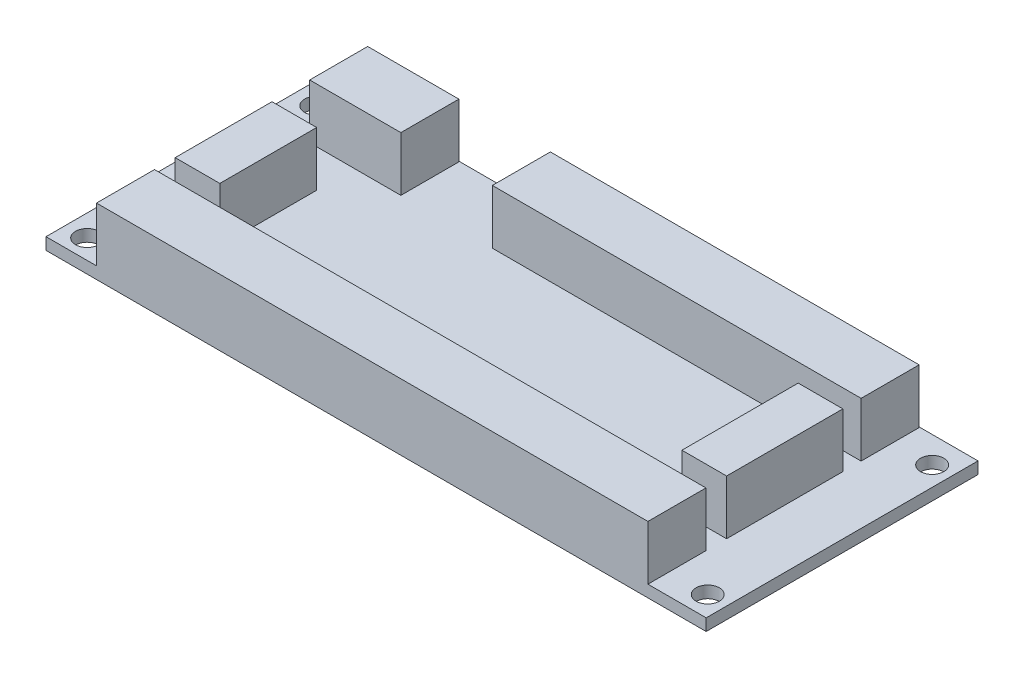
SolidWorks part; units mm, degrees
ref_plane "Front Plane" through (0, 0, 0) normal (0, 0, 1) x (1, 0, 0)
ref_plane "Top Plane" through (0, 0, 0) normal (0, 1, 0) x (1, 0, 0)
ref_plane "Right Plane" through (0, 0, 0) normal (1, 0, 0) x (0, 0, -1)
sketch "Sketch1" plane through (0, 0, 0) normal (0, 1, 0) x (1, 0, 0)
  line L1 (-42.5, -17.5) -> (42.5, -17.5)
  line L2 (-42.5, -17.5) -> (-42.5, 17.5)
  line L3 (-42.5, 17.5) -> (42.5, 17.5)
  line L4 (42.5, -17.5) -> (42.5, 17.5)
  line L5 (-42.5, -17.5) -> (42.5, 17.5) construction
  line L6 (-42.5, 17.5) -> (42.5, -17.5) construction
  circle A0 centre (-39.7, 14.5) radius 1.5
  circle A1 centre (-39.7, -15) radius 1.5
  circle A2 centre (40, 14.1) radius 1.5
  circle A3 centre (40, -14.8) radius 1.5
  point P0 (0, 0)
  dimension "D3" = 3
  dimension "D1" = 85
  dimension "D2" = 35
  dimension "D4" = 3
  dimension "D5" = 2.8
  dimension "D6" = 2.5
  dimension "D7" = 2.8
  dimension "D8" = 3.4
  dimension "D9" = 2.5
  dimension "D10" = 2.7
  dimension "D11" = 2.5
extrude "Boss-Extrude2" add sketch "Sketch1" along normal blind 1.53
sketch "Sketch2" plane through (0, 1.53, 0) normal (0, 1, 0) x (1, 0, 0)
  line L0 (-42.5, -17.5) -> (42.5, -17.5) construction
  line L1 (-36, -17.5) -> (35, -17.5)
  line L2 (-36, -17.5) -> (-36, -10.03)
  line L3 (-36, -10.03) -> (35, -10.03)
  line L4 (35, -17.5) -> (35, -10.03)
  line L5 (-42.5, 17.5) -> (-42.5, -17.5) construction
  line L6 (42.5, -17.5) -> (42.5, 17.5) construction
  line L8 (35, -7.37) -> (29.25, -7.37)
  line L9 (35, -7.37) -> (35, 7.6)
  line L10 (35, 7.6) -> (29.25, 7.6)
  line L11 (29.25, -7.37) -> (29.25, 7.6)
  line L16 (-24.26, 17.42) -> (-36, 17.42)
  line L17 (35, 17.42) -> (-12.48, 17.42)
  line L18 (35, 17.42) -> (35, 9.95)
  line L19 (35, 9.95) -> (-12.48, 9.95)
  line L20 (-12.48, 17.42) -> (-12.48, 9.95)
  line L21 (-24.26, 17.42) -> (-24.26, 9.95)
  line L22 (-24.26, 9.95) -> (-36, 9.95)
  line L23 (-36, 17.42) -> (-36, 9.95)
  line L24 (-36, -7.37) -> (-30.25, -7.37)
  line L25 (-36, -7.37) -> (-36, 5.1)
  line L26 (-36, 5.1) -> (-30.25, 5.1)
  line L27 (-30.25, -7.37) -> (-30.25, 5.1)
  dimension "D1" = 7.47
  dimension "D2" = 6.5
  dimension "D3" = 7.5
  dimension "D4" = 5.75
  dimension "D5" = 2.66
  dimension "D6" = 14.97
  dimension "D7" = 2.35
  dimension "D8" = 47.48
  dimension "D9" = 11.74
  dimension "D10" = 12.47
  dimension "D11" = 2.66
extrude "Boss-Extrude3" add sketch "Sketch2" along normal blind 7
